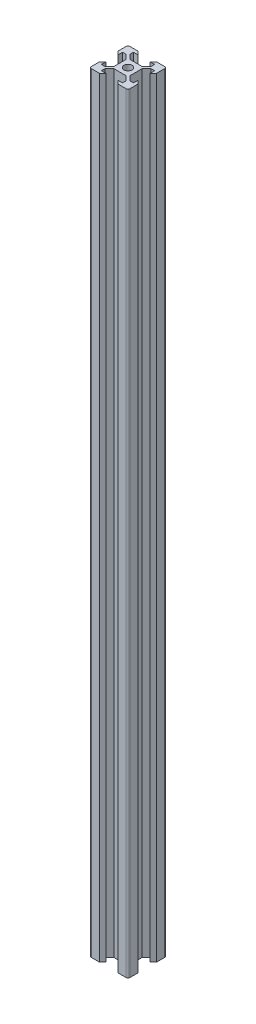
SolidWorks part; units mm, degrees
material "1060 Alloy"
ref_plane "Front Plane" through (0, 0, 0) normal (0, 0, 1) x (1, 0, 0)
ref_plane "Top Plane" through (0, 0, 0) normal (0, 1, 0) x (1, 0, 0)
ref_plane "Right Plane" through (0, 0, 0) normal (1, 0, 0) x (0, 0, -1)
ref_plane "End Plane" through (0, 400, 0) normal (0, 1, 0) x (1, 0, 0)
sketch "MasterLayoutSketch" plane through (0, 0, 0) normal (0, 1, 0) x (1, 0, 0)
  line L0 (-8.325, 3.1) -> (-8.325, 5.5)
  line L1 (-10, -10) -> (10, -10) construction
  line L2 (-10, -10) -> (-10, 10) construction
  line L3 (-10, 10) -> (10, 10) construction
  line L4 (10, -10) -> (10, 10) construction
  line L5 (-10, -10) -> (10, 10) construction
  line L6 (-10, 10) -> (10, -10) construction
  line L7 (-4.775, 10) -> (-3.1, 8.325)
  line L10 (-8.325, 5.5) -> (-6.5607, 5.5)
  line L11 (-10, 4.775) -> (-8.325, 3.1)
  line L12 (-5.5, 8.325) -> (-5.5, 6.5607)
  line L13 (-3.1, 8.325) -> (-5.5, 8.325)
  line L14 (-10, 10) -> (-10, 4.775)
  line L19 (3.1, 8.325) -> (5.5, 8.325)
  line L20 (10, 4.775) -> (8.325, 3.1)
  line L21 (-10, 10) -> (-4.775, 10)
  line L22 (-6.5607, 5.5) -> (-4.1607, 3.1)
  line L23 (-5.5, 6.5607) -> (-3.1, 4.1607)
  line L24 (5.5, 8.325) -> (5.5, 6.5607)
  line L25 (4.775, 10) -> (3.1, 8.325)
  line L26 (8.325, 5.5) -> (6.5607, 5.5)
  line L27 (8.325, 3.1) -> (8.325, 5.5)
  line L28 (10, 10) -> (4.775, 10)
  line L29 (10, 10) -> (10, 4.775)
  line L30 (5.5, 6.5607) -> (3.1, 4.1607)
  line L31 (6.5607, 5.5) -> (4.1607, 3.1)
  line L32 (8.325, -3.1) -> (8.325, -5.5)
  line L33 (4.775, -10) -> (3.1, -8.325)
  line L34 (8.325, -5.5) -> (6.5607, -5.5)
  line L35 (10, -4.775) -> (8.325, -3.1)
  line L36 (5.5, -8.325) -> (5.5, -6.5607)
  line L37 (3.1, -8.325) -> (5.5, -8.325)
  line L38 (10, -10) -> (10, -4.775)
  line L39 (10, -10) -> (4.775, -10)
  line L40 (6.5607, -5.5) -> (4.1607, -3.1)
  line L41 (5.5, -6.5607) -> (3.1, -4.1607)
  line L42 (-3.1, -8.325) -> (-5.5, -8.325)
  line L43 (-10, -4.775) -> (-8.325, -3.1)
  line L44 (-5.5, -8.325) -> (-5.5, -6.5607)
  line L45 (-4.775, -10) -> (-3.1, -8.325)
  line L46 (-8.325, -5.5) -> (-6.5607, -5.5)
  line L47 (-8.325, -3.1) -> (-8.325, -5.5)
  line L48 (-10, -10) -> (-4.775, -10)
  line L49 (-10, -10) -> (-10, -4.775)
  line L50 (-5.5, -6.5607) -> (-3.1, -4.1607)
  line L51 (-6.5607, -5.5) -> (-4.1607, -3.1)
  line L52 (-4.1607, 3.1) -> (-4.1607, -3.1)
  line L53 (-3.1, -4.1607) -> (3.1, -4.1607)
  line L54 (4.1607, -3.1) -> (4.1607, 3.1)
  line L55 (-3.1, 4.1607) -> (3.1, 4.1607)
  circle A0 centre (0, 0) radius 2.1
  point P0 (0, 0)
  point P9 (0, 0)
  dimension "D6" = 4.2
  dimension "D1" = 20
  dimension "D2" = 4
  dimension "D3" = 11
  dimension "D4" = 9.55
  dimension "D5" = 6.2
  dimension "D7" = 1.5
extrude "Main Extrusion" add sketch "MasterLayoutSketch" along normal up to surface (400 mm away) up to plane "End Plane"
cosmetic thread "Cosmetic Thread1" parameters "D1"=11, "D2"=5
cosmetic thread "Cosmetic Thread3" parameters "D1"=11, "D2"=5
fillet "Edge Fillets" radius 1 4 edges at (10, 200, -10) (10, 200, 10) (-10, 200, 10) (-10, 200, -10)
sketch "End Thread Start" plane through (0, 400, 0) normal (0, 1, 0) x (1, 0, 0)
  point P0 (0, 0)
hole_wizard "M5 Tapped Hole1" positions "Sketch3" profile "Sketch4" tap size "M5" standard "ISO"
sketch "Sketch3" plane through (0, 0, 0) normal (0, -1, 0) x (-1, 0, 0)
  point P0 (0, 0)
sketch "Sketch4" plane through (0, 0, 0) normal (1, 0, 0) x (0, 0, -1)
  line L0 (0, 0) -> (0, 13.6618)
  line L1 (0, 13.6618) -> (2.1, 12.4)
  line L2 (2.1, 12.4) -> (2.1, 0)
  line L5 (2.1, 0) -> (0, 0)
  line L10 (0, 13.6618) -> (-2.1, 12.4) construction
  line L11 (0, -6.35) -> (0, 107.95) construction
  dimension "Tap Drill Dia." = 4.2
  dimension "Tap Drill Depth" = 12.4
  dimension "Drill Angle" = 118
